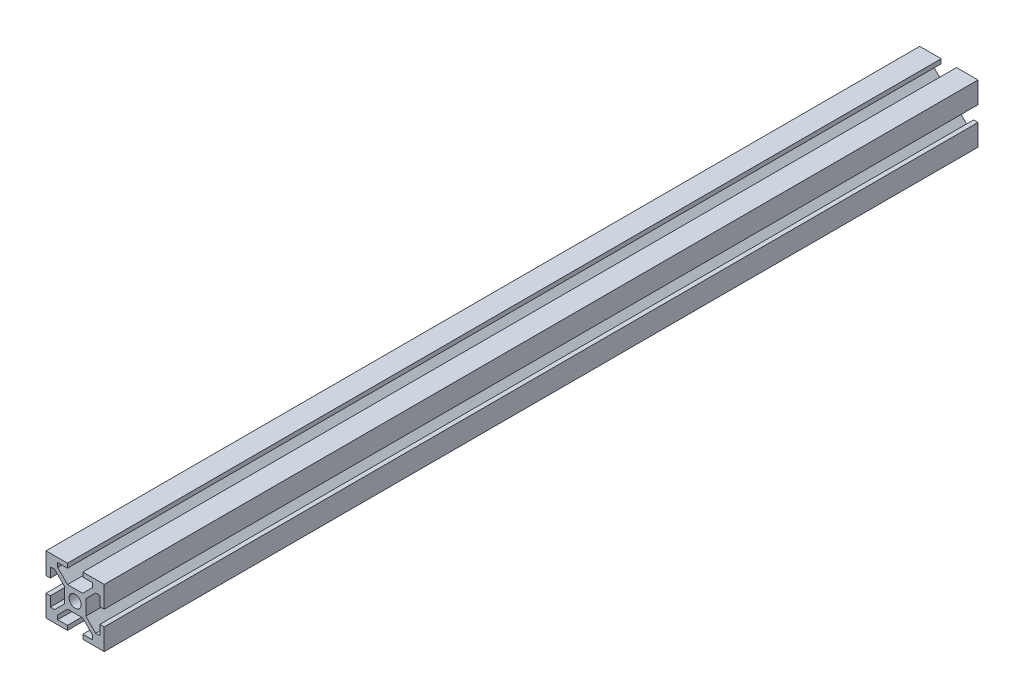
SolidWorks part; units mm, degrees
ref_plane "Plan de face" through (0, 0, 0) normal (0, 0, 1) x (1, 0, 0)
ref_plane "Plan de dessus" through (0, 0, 0) normal (0, 1, 0) x (1, 0, 0)
ref_plane "Plan de droite" through (0, 0, 0) normal (1, 0, 0) x (0, 0, -1)
sketch "Esquisse1" plane through (0, 0, 0) normal (0, 0, 1) x (1, 0, 0)
  line L0 (-6.2433, 16.5527) -> (-3.644, 16.5527)
  line L1 (-6.2433, 12.8927) -> (-2.5833, 12.8927)
  line L2 (-6.2433, 12.8927) -> (-6.2433, 16.5527)
  line L3 (-3.6133, 22.8927) -> (3.7567, 22.8927)
  line L4 (3.7567, 15.5227) -> (3.7567, 22.8927)
  line L5 (-2.5833, 15.4921) -> (-2.5833, 12.8927)
  line L6 (-2.5833, 16.5527) -> (3.7567, 22.8927) construction
  line L7 (-3.644, 16.5527) -> (-0.2483, 19.9484)
  line L8 (-0.2483, 19.9484) -> (-0.2483, 21.3927)
  line L9 (-0.2483, 21.3927) -> (-3.6133, 21.3927)
  line L10 (-3.6133, 21.3927) -> (-3.6133, 22.8927)
  line L11 (-2.5833, 15.4921) -> (0.8123, 18.8877)
  line L12 (0.8123, 18.8877) -> (2.2567, 18.8877)
  line L13 (2.2567, 18.8877) -> (2.2567, 15.5227)
  line L14 (2.2567, 15.5227) -> (3.7567, 15.5227)
  line L15 (-0.2483, 19.9484) -> (0.282, 19.4181) construction
  line L16 (0.282, 19.4181) -> (0.8123, 18.8877) construction
  line L17 (-6.2433, 16.5527) -> (-6.2433, 22.8927) construction
  line L18 (-2.5833, 12.8927) -> (3.7567, 12.8927) construction
  line L19 (-6.2433, 22.8927) -> (-3.6133, 22.8927) construction
  line L20 (3.7567, 12.8927) -> (3.7567, 15.5227) construction
  line L21 (-3.644, 16.5527) -> (-2.5833, 16.5527) construction
  line L22 (-2.5833, 16.5527) -> (-2.5833, 15.4921) construction
  line L23 (-2.5833, 12.8927) -> (-2.5833, 10.2934)
  line L24 (-6.2433, 12.8927) -> (-6.2433, 9.2327)
  line L25 (-6.2433, 12.8927) -> (-2.5833, 12.8927)
  line L26 (3.7567, 10.2627) -> (3.7567, 2.8927)
  line L27 (-3.6133, 2.8927) -> (3.7567, 2.8927)
  line L28 (-3.644, 9.2327) -> (-6.2433, 9.2327)
  line L29 (-2.5833, 9.2327) -> (3.7567, 2.8927) construction
  line L30 (-2.5833, 10.2934) -> (0.8123, 6.8977)
  line L31 (0.8123, 6.8977) -> (2.2567, 6.8977)
  line L32 (2.2567, 6.8977) -> (2.2567, 10.2627)
  line L33 (2.2567, 10.2627) -> (3.7567, 10.2627)
  line L34 (-3.644, 9.2327) -> (-0.2483, 5.8371)
  line L35 (-0.2483, 5.8371) -> (-0.2483, 4.3927)
  line L36 (-0.2483, 4.3927) -> (-3.6133, 4.3927)
  line L37 (-3.6133, 4.3927) -> (-3.6133, 2.8927)
  line L38 (0.8123, 6.8977) -> (0.282, 6.3674) construction
  line L39 (0.282, 6.3674) -> (-0.2483, 5.8371) construction
  line L40 (-2.5833, 12.8927) -> (3.7567, 12.8927) construction
  line L41 (-6.2433, 9.2327) -> (-6.2433, 2.8927) construction
  line L42 (3.7567, 12.8927) -> (3.7567, 10.2627) construction
  line L43 (-6.2433, 2.8927) -> (-3.6133, 2.8927) construction
  line L44 (-2.5833, 10.2934) -> (-2.5833, 9.2327) construction
  line L45 (-2.5833, 9.2327) -> (-3.644, 9.2327) construction
  line L46 (-6.2433, 9.2327) -> (-8.8427, 9.2327)
  line L47 (-6.2433, 12.8927) -> (-9.9033, 12.8927)
  line L48 (-6.2433, 12.8927) -> (-6.2433, 9.2327)
  line L49 (-8.8733, 2.8927) -> (-16.2433, 2.8927)
  line L50 (-16.2433, 10.2627) -> (-16.2433, 2.8927)
  line L51 (-9.9033, 10.2934) -> (-9.9033, 12.8927)
  line L52 (-9.9033, 9.2327) -> (-16.2433, 2.8927) construction
  line L53 (-8.8427, 9.2327) -> (-12.2383, 5.8371)
  line L54 (-12.2383, 5.8371) -> (-12.2383, 4.3927)
  line L55 (-12.2383, 4.3927) -> (-8.8733, 4.3927)
  line L56 (-8.8733, 4.3927) -> (-8.8733, 2.8927)
  line L57 (-9.9033, 10.2934) -> (-13.299, 6.8977)
  line L58 (-13.299, 6.8977) -> (-14.7433, 6.8977)
  line L59 (-14.7433, 6.8977) -> (-14.7433, 10.2627)
  line L60 (-14.7433, 10.2627) -> (-16.2433, 10.2627)
  line L61 (-12.2383, 5.8371) -> (-12.7686, 6.3674) construction
  line L62 (-12.7686, 6.3674) -> (-13.299, 6.8977) construction
  line L63 (-6.2433, 9.2327) -> (-6.2433, 2.8927) construction
  line L64 (-9.9033, 12.8927) -> (-16.2433, 12.8927) construction
  line L65 (-6.2433, 2.8927) -> (-8.8733, 2.8927) construction
  line L66 (-16.2433, 12.8927) -> (-16.2433, 10.2627) construction
  line L67 (-8.8427, 9.2327) -> (-9.9033, 9.2327) construction
  line L68 (-9.9033, 9.2327) -> (-9.9033, 10.2934) construction
  line L69 (-9.9033, 12.8927) -> (-9.9033, 15.4921)
  line L70 (-6.2433, 12.8927) -> (-6.2433, 16.5527)
  line L71 (-6.2433, 12.8927) -> (-9.9033, 12.8927)
  line L72 (-16.2433, 15.5227) -> (-16.2433, 22.8927)
  line L73 (-8.8733, 22.8927) -> (-16.2433, 22.8927)
  line L74 (-8.8427, 16.5527) -> (-6.2433, 16.5527)
  line L75 (-9.9033, 16.5527) -> (-16.2433, 22.8927) construction
  line L76 (-9.9033, 15.4921) -> (-13.299, 18.8877)
  line L77 (-13.299, 18.8877) -> (-14.7433, 18.8877)
  line L78 (-14.7433, 18.8877) -> (-14.7433, 15.5227)
  line L79 (-14.7433, 15.5227) -> (-16.2433, 15.5227)
  line L80 (-8.8427, 16.5527) -> (-12.2383, 19.9484)
  line L81 (-12.2383, 19.9484) -> (-12.2383, 21.3927)
  line L82 (-12.2383, 21.3927) -> (-8.8733, 21.3927)
  line L83 (-8.8733, 21.3927) -> (-8.8733, 22.8927)
  line L84 (-13.299, 18.8877) -> (-12.7686, 19.4181) construction
  line L85 (-12.7686, 19.4181) -> (-12.2383, 19.9484) construction
  line L86 (-9.9033, 12.8927) -> (-16.2433, 12.8927) construction
  line L87 (-6.2433, 16.5527) -> (-6.2433, 22.8927) construction
  line L88 (-16.2433, 12.8927) -> (-16.2433, 15.5227) construction
  line L89 (-6.2433, 22.8927) -> (-8.8733, 22.8927) construction
  line L90 (-9.9033, 15.4921) -> (-9.9033, 16.5527) construction
  line L91 (-9.9033, 16.5527) -> (-8.8427, 16.5527) construction
  circle A0 centre (-6.2433, 12.8927) radius 2.095
  point P72 (-6.2433, 12.8927)
  dimension "D1" = 10
  dimension "D2" = 3.66
  dimension "D3" = 1.5
  dimension "D4" = 2.63
  dimension "D5" = 1.5
  dimension "D6" = 5.995
  dimension "D7" = 4
extrude "Boss.-Extru.1" add sketch "Esquisse1" along normal blind 300 contours A0 L70 L74 L80 L81 L82 L83 L73 L72 L79 L78 L77 L76 L69 L71 | A0 L25 L5 L11 L12 L13 L14 L4 L3 L10 L9 L8 L7 L0 L70 | A0 L48 L28 L34 L35 L36 L37 L27 L26 L33 L32 L31 L30 L23 L25 | A0 L71 L51 L57 L58 L59 L60 L50 L49 L56 L55 L54 L53 L46 L48
